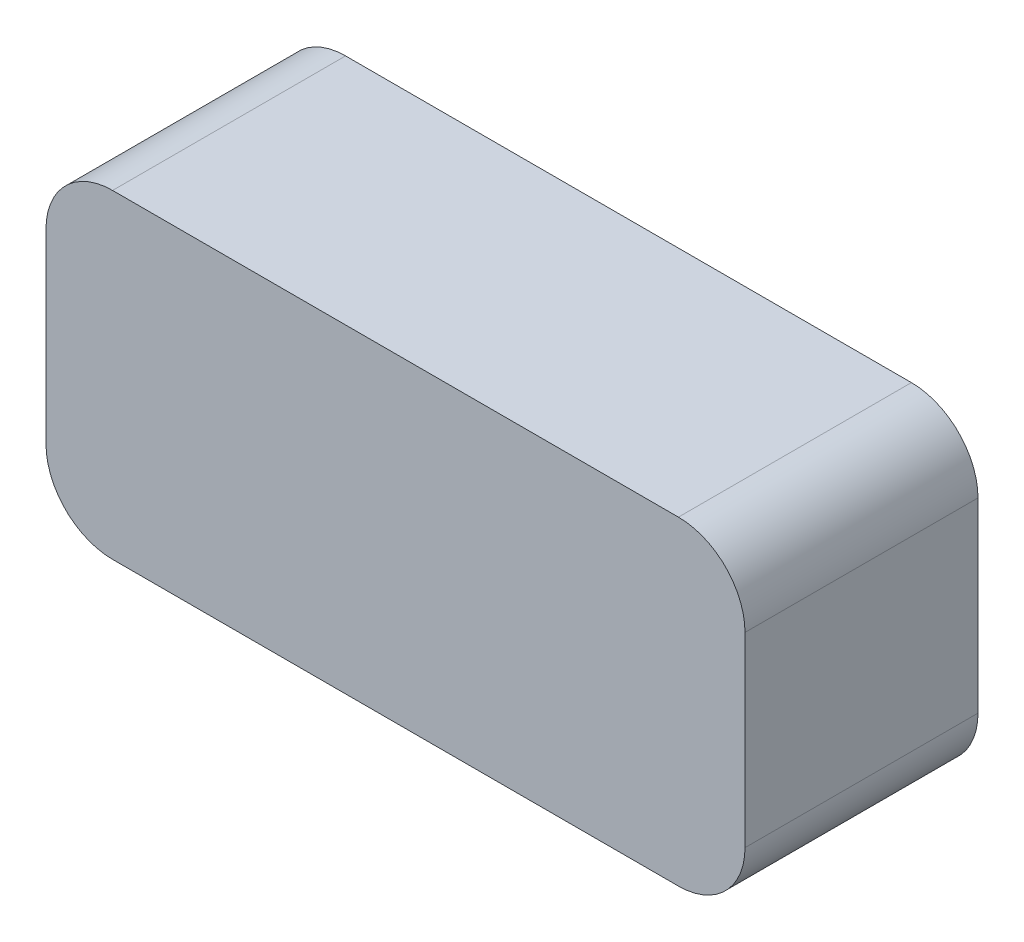
SolidWorks part; units mm, degrees
ref_plane "Front Plane" through (0, 0, 0) normal (0, 0, 1) x (1, 0, 0)
ref_plane "Top Plane" through (0, 0, 0) normal (0, 1, 0) x (1, 0, 0)
ref_plane "Right Plane" through (0, 0, 0) normal (1, 0, 0) x (0, 0, -1)
sketch "S01 - Captured tail button" plane through (0, 0, 0) normal (0, 0, 1) x (1, 0, 0)
  line L0 (-8.5, -5) -> (8.5, -5)
  line L1 (10.5, -3) -> (10.5, 2.6)
  line L2 (8.5, 4.6) -> (-8.5, 4.6)
  line L3 (-10.5, 2.6) -> (-10.5, -3)
  arc A0 (8.5, -5) -> (10.5, -3) centre (8.5, -3) ccw
  arc A1 (10.5, 2.6) -> (8.5, 4.6) centre (8.5, 2.6) ccw
  arc A2 (-8.5, 4.6) -> (-10.5, 2.6) centre (-8.5, 2.6) ccw
  arc A3 (-10.5, -3) -> (-8.5, -5) centre (-8.5, -3) ccw
  dimension "D1" = 2
  dimension "D2" = 10.5
  dimension "D3" = 10.5
  dimension "D4" = 4.6
  dimension "D5" = 5
extrude "01 - Captured tail button" add sketch "S01 - Captured tail button" along normal blind 7
